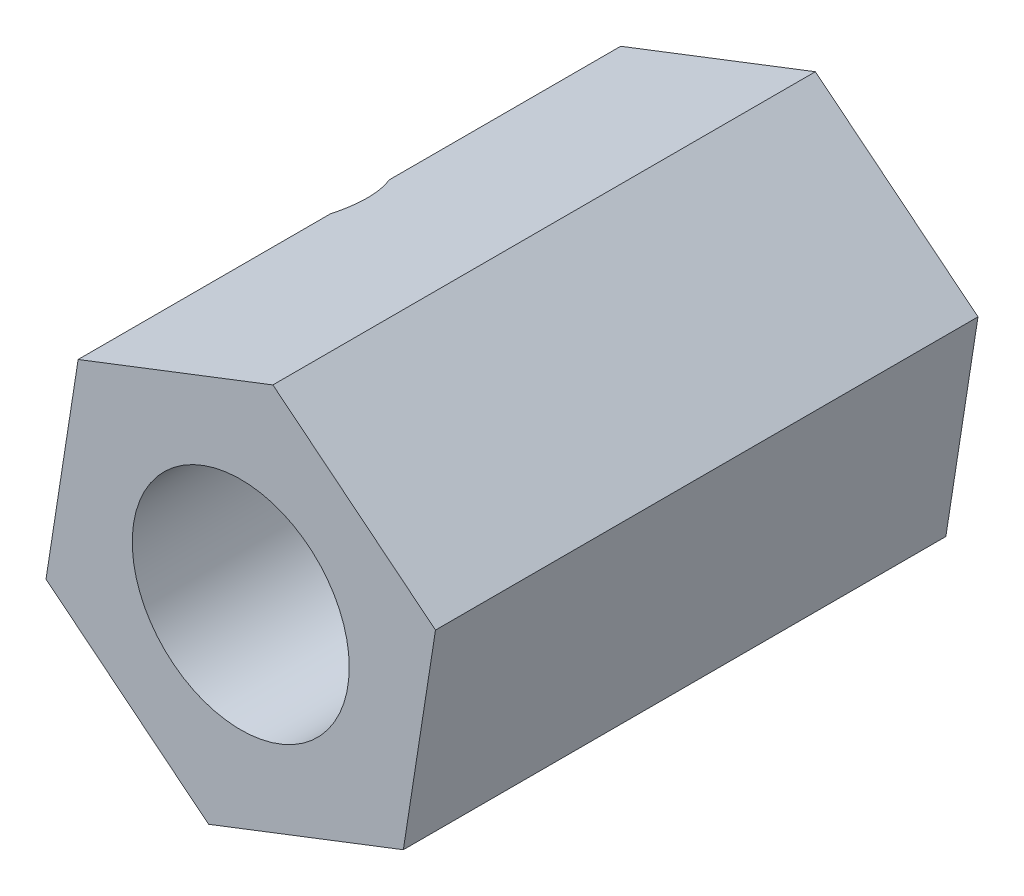
SolidWorks part; units mm, degrees
ref_plane "Спереди" through (0, 0, 0) normal (0, 0, 1) x (1, 0, 0)
ref_plane "Сверху" through (0, 0, 0) normal (0, 1, 0) x (1, 0, 0)
ref_plane "Справа" through (0, 0, 0) normal (1, 0, 0) x (0, 0, -1)
sketch "Эскиз1" plane through (0, 0, 0) normal (0, 0, 1) x (1, 0, 0)
  line L1 (8.9923, -7.2438) -> (10.7694, 4.1657)
  line L2 (10.7694, 4.1657) -> (1.7772, 11.4094)
  line L3 (1.7772, 11.4094) -> (-8.9923, 7.2438)
  line L4 (-8.9923, 7.2438) -> (-10.7694, -4.1657)
  line L5 (-10.7694, -4.1657) -> (-1.7772, -11.4094)
  line L6 (-1.7772, -11.4094) -> (8.9923, -7.2438)
  circle A0 centre (0, 0) radius 10 construction
  dimension "D1" = 20
extrude "Бобышка-Вытянуть1" add sketch "Эскиз1" along normal blind 30
sketch "Эскиз2" plane through (0, 0, 30) normal (0, 0, 1) x (1, 0, 0)
  circle A0 centre (0, 0) radius 6
extrude "Вырез-Вытянуть1" cut sketch "Эскиз2" against normal through all
sketch "Эскиз4" plane through (-9.8809, 1.5391, 0) normal (-0.9881, 0.1539, 0) x (0, 0, 1)
  circle A0 centre (14.4252, 0) radius 6
extrude "Вырез-Вытянуть2" cut sketch "Эскиз4" against normal blind 3
